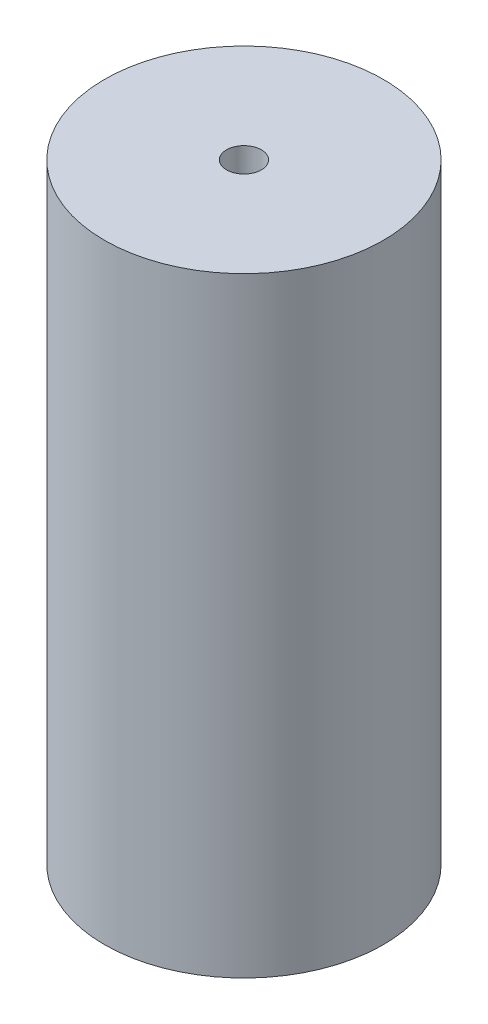
SolidWorks part; units mm, degrees
ref_plane "前视基准面" through (0, 0, 0) normal (0, 0, 1) x (1, 0, 0)
ref_plane "上视基准面" through (0, 0, 0) normal (0, 1, 0) x (1, 0, 0)
ref_plane "右视基准面" through (0, 0, 0) normal (1, 0, 0) x (0, 0, -1)
other "Configuration Table"
sketch "草图1" plane through (0, 0, 0) normal (0, 1, 0) x (1, 0, 0)
  circle A1 centre (0, 0) radius 5
  circle A2 centre (0, 0) radius 40
extrude "凸台-拉伸1" add sketch "草图1" along normal blind 175
